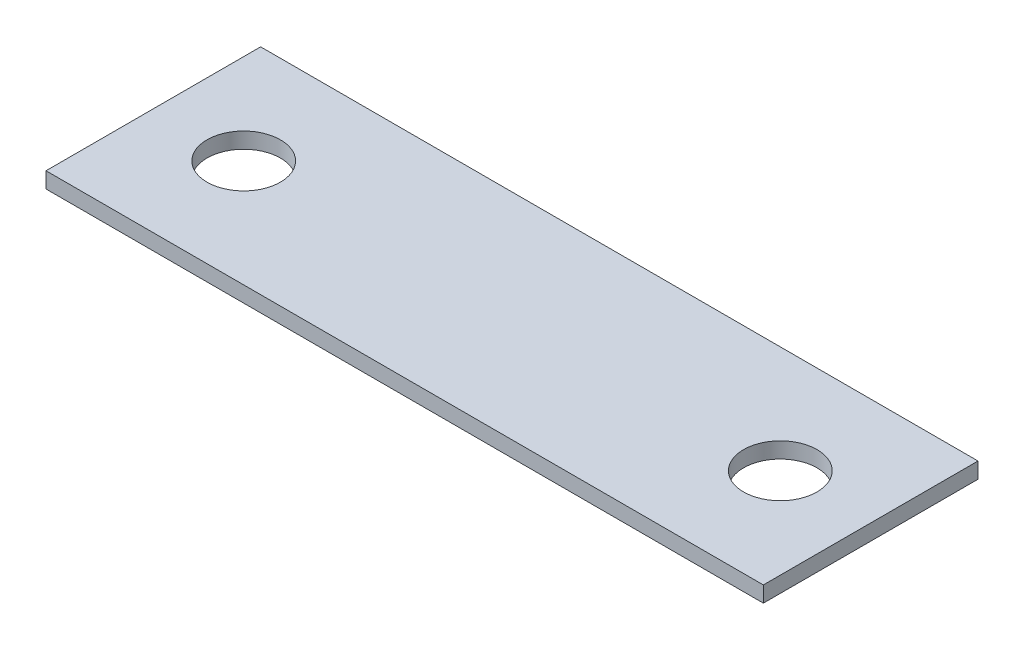
SolidWorks part; units mm, degrees
ref_plane "Front Plane" through (0, 0, 0) normal (0, 0, 1) x (1, 0, 0)
ref_plane "Top Plane" through (0, 0, 0) normal (0, 1, 0) x (1, 0, 0)
ref_plane "Right Plane" through (0, 0, 0) normal (1, 0, 0) x (0, 0, -1)
sketch "Sketch1" plane through (0, 0, 0) normal (0, 1, 0) x (1, 0, 0)
  line L0 (0, 19) -> (0, -19) construction
  line L1 (-63.5, 19) -> (63.5, 19)
  line L2 (-63.5, 19) -> (-63.5, -19)
  line L3 (-63.5, -19) -> (63.5, -19)
  line L4 (63.5, 19) -> (63.5, -19)
  line L5 (-63.5, 19) -> (63.5, -19) construction
  line L6 (-63.5, -19) -> (63.5, 19) construction
  circle A0 centre (-47.5, 0) radius 6.5
  circle A2 centre (47.5, 0) radius 6.5
  point P0 (0, 0)
  dimension "D3" = 13
  dimension "D1" = 38
  dimension "D2" = 127
  dimension "D4" = 47.5
extrude "Boss-Extrude1" add sketch "Sketch1" along normal blind 2.8
